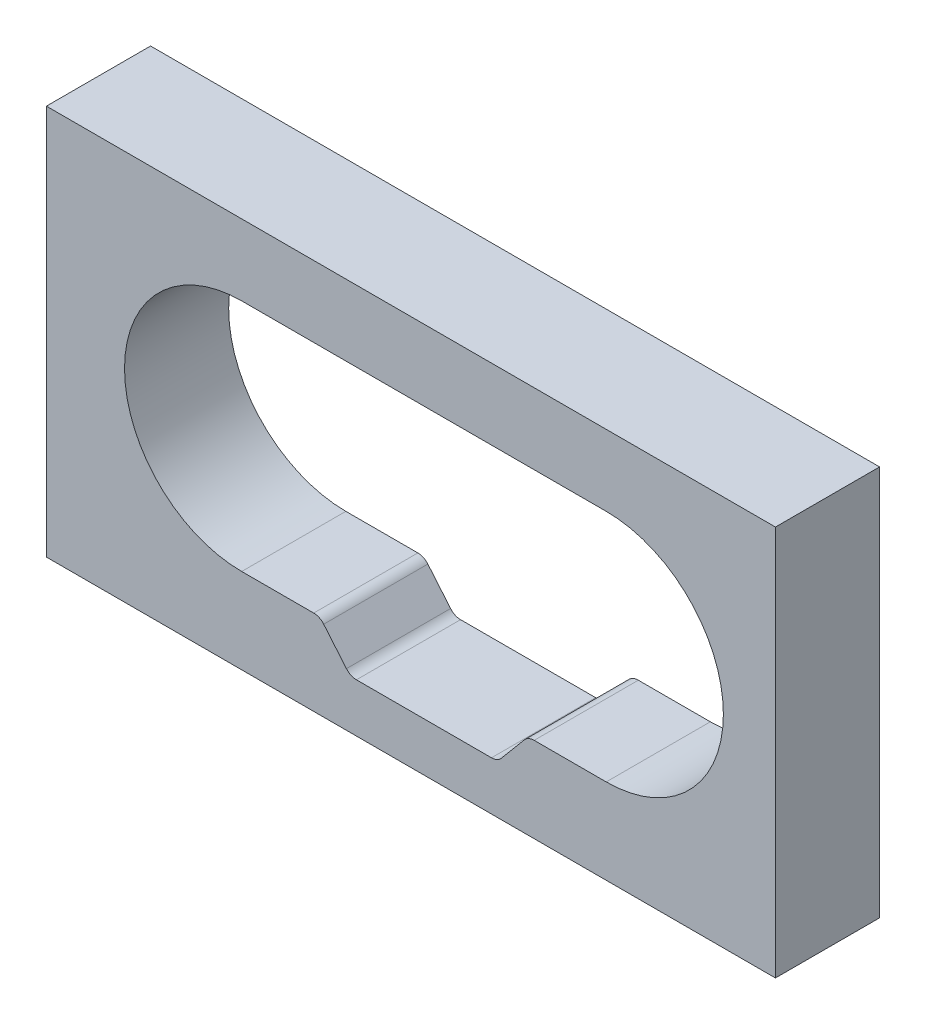
SolidWorks part; units mm, degrees
ref_plane "前视基准面" through (0, 0, 0) normal (0, 0, 1) x (1, 0, 0)
ref_plane "上视基准面" through (0, 0, 0) normal (0, 1, 0) x (1, 0, 0)
ref_plane "右视基准面" through (0, 0, 0) normal (1, 0, 0) x (0, 0, -1)
other "Configuration Table"
sketch "草图1" plane through (0, 0, 0) normal (0, 0, 1) x (1, 0, 0)
  line L0 (0, 0) -> (28, 0) construction
  line L1 (0, 9) -> (28, 9)
  line L10 (17.1649, -6.6117) -> (10.3449, -6.6117) construction
  line L11 (19.1649, -9.0117) -> (19.1649, -8.6117) construction
  line L12 (8.3449, -8.6117) -> (8.3449, -9.0117) construction
  line L13 (10.3449, -11.0117) -> (17.1649, -11.0117) construction
  line L14 (0, -9) -> (6, -9)
  line L15 (6, -9) -> (8.3449, -11.8)
  line L18 (8.3449, -11.8) -> (19.6551, -11.8)
  line L19 (14, -9) -> (14, -11.8) construction
  line L20 (22, -9) -> (19.6551, -11.8)
  line L21 (28, -9) -> (22, -9)
  line L22 (-15, 14.456) -> (41, 14.456)
  line L23 (-15, 14.456) -> (-15, -15.544)
  line L24 (-15, -15.544) -> (41, -15.544)
  line L25 (41, 14.456) -> (41, -15.544)
  arc A0 (0, 9) -> (0, -9) centre (0, 0) ccw
  arc A1 (28, -9) -> (28, 9) centre (28, 0) ccw
  arc A12 (19.1649, -8.6117) -> (17.1649, -6.6117) centre (17.1649, -8.6117) ccw construction
  arc A13 (17.1649, -11.0117) -> (19.1649, -9.0117) centre (17.1649, -9.0117) ccw construction
  arc A14 (10.3449, -6.6117) -> (8.3449, -8.6117) centre (10.3449, -8.6117) ccw construction
  arc A15 (8.3449, -9.0117) -> (10.3449, -11.0117) centre (10.3449, -9.0117) ccw construction
  circle A16 centre (0.7549, -0.8917) radius 8 construction
  circle A17 centre (26.7549, -0.8917) radius 8 construction
  circle A18 centre (0.7549, -0.8917) radius 7.6 construction
  circle A19 centre (26.7549, -0.8917) radius 7.6 construction
  circle A20 centre (-7.6551, 7.9783) radius 0.8 construction
  circle A21 centre (-7.6551, -9.7617) radius 0.8 construction
  circle A22 centre (35.1649, 7.9783) radius 0.8 construction
  circle A23 centre (35.1649, -9.7617) radius 0.8 construction
  point P3 (14, 0)
  point P15 (14, -9)
  dimension "D7" = 9
  dimension "D5" = 6
  dimension "D6" = 56
  dimension "D1" = 18
  dimension "D2" = 28
  dimension "D3" = 15
  dimension "D4" = 30
  dimension "D8" = 14
  dimension "D9" = 2.8
extrude "凸台-拉伸1" add sketch "草图1" along normal blind 8
fillet "圆角1" radius 1 4 edges at (22, -9, 4) (19.6551, -11.8, 4) (6, -9, 4) (8.3449, -11.8, 4)
